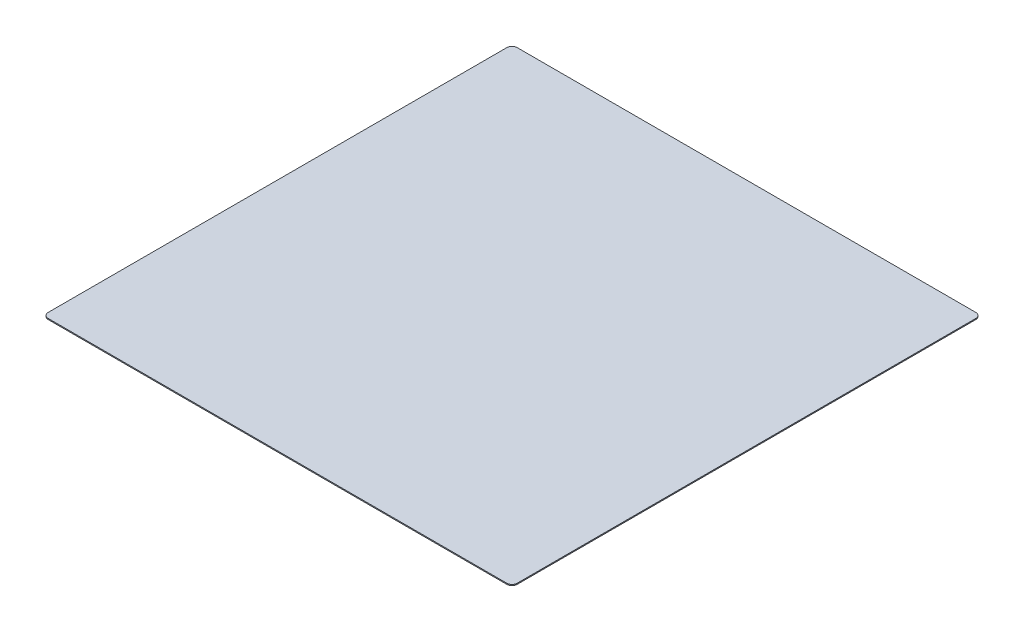
SolidWorks part; units mm, degrees
material "Kapton"
ref_plane "Front Plane" through (0, 0, 0) normal (0, 0, 1) x (1, 0, 0)
ref_plane "Top Plane" through (0, 0, 0) normal (0, 1, 0) x (1, 0, 0)
ref_plane "Right Plane" through (0, 0, 0) normal (1, 0, 0) x (0, 0, -1)
sketch "Sketch1" plane through (0, 0, 0) normal (0, 1, 0) x (1, 0, 0)
  line L1 (-68.35, -68.35) -> (68.35, -68.35)
  line L2 (-68.35, -68.35) -> (-68.35, 68.35)
  line L3 (-68.35, 68.35) -> (68.35, 68.35)
  line L4 (68.35, -68.35) -> (68.35, 68.35)
  line L5 (-68.35, -68.35) -> (68.35, 68.35) construction
  line L6 (-68.35, 68.35) -> (68.35, -68.35) construction
  point P0 (0, 0)
  dimension "D1" = 136.7
extrude "Boss-Extrude1" add sketch "Sketch1" along normal mid plane 0.3
fillet "Fillet1" radius 1.5 4 edges at (-68.35, 0, 68.35) (-68.35, 0, -68.35) (68.35, 0, -68.35) (68.35, 0, 68.35)
sketch "Sketch2" plane through (0, 0.15, 0) normal (0, 1, 0) x (1, 0, 0)
  text T0 "EDS PCB LFG BOIZ"
equation "\"panel_width\"= 5.5in"
equation "\"finger_joint_width\"= 30mm"
equation "\"D1@Sketch1\"=\"panel_width\" - 3mm"
